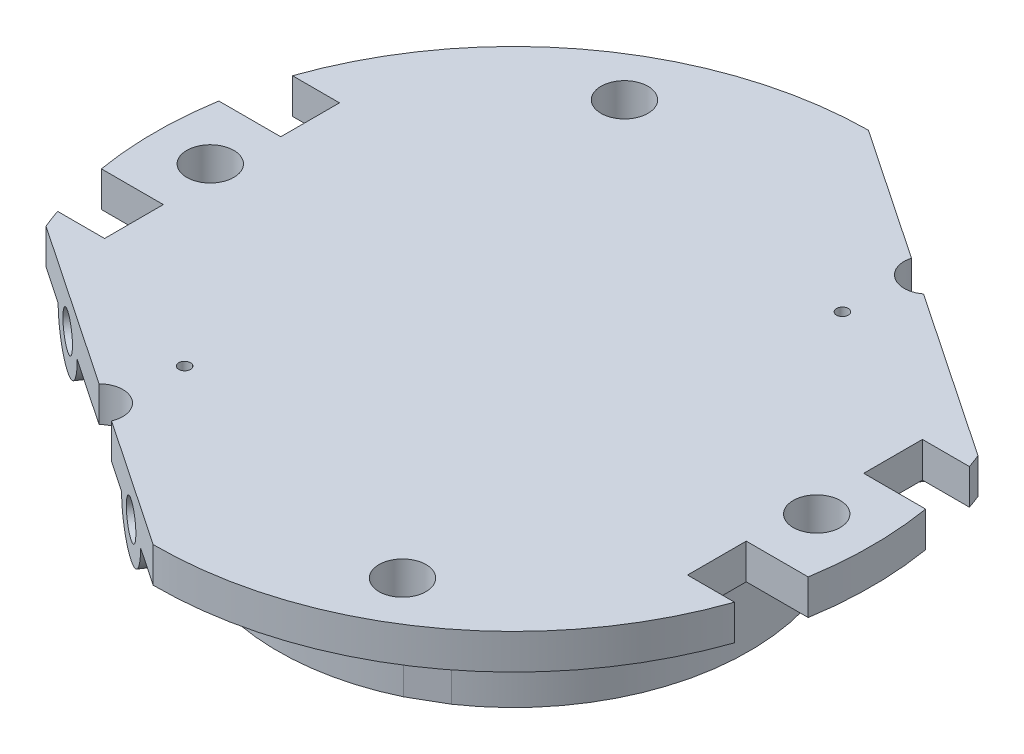
SolidWorks part; units mm, degrees
ref_plane "Alzado" through (0, 0, 0) normal (0, 0, 1) x (1, 0, 0)
ref_plane "Planta" through (0, 0, 0) normal (0, 1, 0) x (1, 0, 0)
ref_plane "Vista lateral" through (0, 0, 0) normal (1, 0, 0) x (0, 0, -1)
sketch "Croquis1" plane through (0, 0, 0) normal (0, 1, 0) x (1, 0, 0)
  circle A0 centre (0, 0) radius 30.5
extrude "Saliente-Extruir1" add sketch "Croquis1" along normal blind 3
sketch "Croquis5" plane through (0, 3, 0) normal (0, 1, 0) x (1, 0, 0)
  line L1 (28.8141, -5) -> (30.0874, -5)
  line L2 (28.8141, 5) -> (30.0874, 5)
  line L3 (-24.8141, 10) -> (-28.8141, 10)
  line L4 (24.8141, -5) -> (24.8141, -10)
  line L5 (-24.8141, -10) -> (-28.8141, -10)
  line L6 (24.8141, -5) -> (28.8141, -5)
  line L7 (24.8141, 5) -> (24.8141, 10)
  line L8 (-24.8141, 5) -> (-28.8141, 5)
  line L9 (-24.8141, 5) -> (-24.8141, 10)
  line L10 (-24.8141, -5) -> (-28.8141, -5)
  line L11 (-24.8141, -5) -> (-24.8141, -10)
  line L12 (24.8141, 5) -> (28.8141, 5)
  line L13 (24.8141, -10) -> (28.8141, -10)
  line L14 (24.8141, 10) -> (28.8141, 10)
  line L15 (-28.8141, 5) -> (-30.0874, 5)
  line L16 (-28.8141, -5) -> (-30.0874, -5)
  line L18 (-24.8141, 0) -> (-12.407, -21.4896)
  line L19 (-12.407, -21.4896) -> (12.407, -21.4896)
  line L20 (12.407, -21.4896) -> (24.8141, 0)
  line L21 (24.8141, 0) -> (12.407, 21.4896)
  line L22 (12.407, 21.4896) -> (-12.407, 21.4896)
  line L23 (-12.407, 21.4896) -> (-24.8141, 0)
  circle A0 centre (0, 0) radius 21.4896 construction
  circle A1 centre (0, 0) radius 30.5 construction
  arc A2 (-28.8141, 10) -> (-30.0874, 5) centre (0, 0) ccw
  arc A4 (-30.0874, -5) -> (-28.8141, -10) centre (0, 0) ccw
  arc A5 (30.0874, -5) -> (28.8141, -10) centre (0, 0) cw
  arc A6 (28.8141, 10) -> (30.0874, 5) centre (0, 0) cw
  circle M2 centre (0, 0) radius 30.5
extrude "Cortar-Extruir3" cut sketch "Croquis5" against normal blind 4 contours L10 L16 L5 L11 M2 | L15 L8 L9 L3 M2 | L14 L7 L12 L2 M2 | L4 L13 L1 L6 M2
sketch "Croquis7" plane through (0, 3, 0) normal (0, 1, 0) x (1, 0, 0)
  line L2 (25.8141, 0) -> (12.907, 22.3556)
  line L3 (12.907, 22.3556) -> (-12.907, 22.3556)
  line L4 (-12.907, 22.3556) -> (-25.8141, 0)
  line L5 (-25.8141, 0) -> (-12.907, -22.3556)
  line L6 (-12.907, -22.3556) -> (12.907, -22.3556)
  line L7 (12.907, -22.3556) -> (25.8141, 0)
  circle A0 centre (25.8141, 0) radius 2
  circle A4 centre (-25.8141, 0) radius 2
  circle A5 centre (0, 0) radius 22.3556 construction
  circle A6 centre (12.907, 22.3556) radius 2
  circle A7 centre (-12.907, -22.3556) radius 2
  circle A8 centre (-12.907, 22.3556) radius 2
  circle A9 centre (12.907, -22.3556) radius 2
extrude "Cortar-Extruir4" cut sketch "Croquis7" against normal blind 10 contours A8 L4 L3 | A4 L4 L5 | A4 L5 L4 | A8 L3 L4 | L2 A6 L3 | L3 A6 L2 | L7 A0 L2 | L2 A0 L7 | A7 L5 L6 | A7 L6 L5 | L6 A9 L7 | L7 A9 L6
sketch "Croquis8" plane through (0, 3, 0) normal (0, 1, 0) x (1, 0, 0)
  line L0 (0, 0) -> (12, 0)
  line L1 (12, 0) -> (12, 16)
  line L2 (0, 0) -> (-12, 0)
  line L3 (-12, 0) -> (-12, -16)
  circle A0 centre (12, 16) radius 0.5
  circle A1 centre (-12, -16) radius 0.5
extrude "Cortar-Extruir5" cut sketch "Croquis8" against normal blind 3
sketch "Croquis9" plane through (0, 3, 0) normal (0, 1, 0) x (1, 0, 0)
  line L2 (-10, 17.3205) -> (-8.701, 18.0705)
  line L5 (25.6318, 16.5306) -> (27.1318, 13.9325)
  line L6 (-10, 17.3205) -> (-11.299, 16.5705)
  line L8 (10, -17.3205) -> (8.701, -18.0705)
  line L9 (10, -17.3205) -> (11.299, -16.5705)
  circle A0 centre (0, 0) radius 20.0562
  circle A1 centre (-12, -16) radius 3
  circle A2 centre (12, 16) radius 3
extrude "Saliente-Extruir2" add sketch "Croquis9" against normal blind 13
sketch "Croquis11" plane through (14.0495, 0, -20.8293) normal (0.5592, 0, -0.829) x (-0.829, 0, -0.5592)
  line L1 (17.2916, 0) -> (-17.2916, 0)
  line L2 (17.2916, 0) -> (17.2916, 3)
  line L3 (17.2916, 3) -> (-17.2916, 3)
  line L4 (-17.2916, 0) -> (-17.2916, 3)
extrude "Saliente-Extruir3" add sketch "Croquis11" along normal blind 6
sketch "Croquis12" plane through (0, 3, 0) normal (0, 1, 0) x (1, 0, 0)
  circle A0 centre (12.907, 22.3556) radius 2
extrude "Cortar-Extruir7" cut sketch "Croquis12" against normal blind 3
sketch "Croquis13" plane through (17.4047, 0, -25.8035) normal (0.5592, 0, -0.829) x (-0.829, 0, -0.5592)
  line L0 (-17.2916, 0) -> (17.2916, 0)
  line L1 (17.2916, 3) -> (-17.2916, 3)
  line L2 (17.2916, 3) -> (-17.2916, 3) construction
  line L3 (17.2916, 0) -> (17.2916, 3) construction
  circle A1 centre (10, 0) radius 3
  circle A2 centre (-10, 0) radius 3
  circle A3 centre (10, 0) radius 1.5
  circle A5 centre (-10, 0) radius 1.5
  line M4 (-17.2916, 0) -> (17.2916, 0)
extrude "Saliente-Extruir4" add sketch "Croquis13" against normal blind 20 contours A3 L0 A1 | A3 L0 A1 | A5 L0 A2 | A5 L0 A2 | A5 M4 | A3 M4
sketch "Croquis14" plane through (17.4047, 0, -25.8035) normal (0.5592, 0, -0.829) x (-0.829, 0, -0.5592)
  circle A0 centre (-10, 0) radius 1.5
  circle A1 centre (10, 0) radius 1.5
extrude "Cortar-Extruir8" cut sketch "Croquis14" against normal blind 6
sketch "Croquis15" plane through (0, 3, 0) normal (0, 1, 0) x (1, 0, 0)
  line L0 (28.3849, 11.16) -> (-0.2859, 30.4987)
  line L1 (28.3849, 11.16) -> (0.1409, -30.7136)
  line L2 (-0.2859, 30.4987) -> (-28.5299, -11.3749)
  line L3 (0.1409, -30.7136) -> (-28.5299, -11.3749)
  circle A0 centre (-0.2859, 0) radius 30.7165
  arc M12 (-28.8141, -10) -> (28.8141, -10) centre (0, 0) ccw
  circle M28 centre (-12.907, -22.3556) radius 2
extrude "Cortar-Extruir9" cut sketch "Croquis15" against normal blind 3 contours L3 M12 M28
sketch "Croquis16" plane through (-14.1945, 0, 21.0442) normal (-0.5592, 0, 0.829) x (0.829, 0, 0.5592)
  line L0 (-16.9088, 0) -> (-16.9088, 3)
  line L1 (-16.9088, 0) -> (16.78, 0)
  line L2 (-16.9088, 3) -> (16.78, 3)
  line L3 (16.78, 0) -> (16.78, 3)
extrude "Saliente-Extruir5" add sketch "Croquis16" along normal blind 6
sketch "Croquis17" plane through (0, 3, 0) normal (0, 1, 0) x (1, 0, 0)
  circle A0 centre (-12.907, -22.3556) radius 2
extrude "Cortar-Extruir10" cut sketch "Croquis17" against normal blind 3
sketch "Croquis18" plane through (-17.5497, 0, 26.0185) normal (-0.5592, 0, 0.829) x (0.829, 0, 0.5592)
  line L2 (-16.9088, 0) -> (16.78, 0) construction
  circle A0 centre (9.9356, 0) radius 3
  circle A1 centre (-10.0644, 0) radius 3
extrude "Saliente-Extruir6" add sketch "Croquis18" against normal blind 25
sketch "Croquis19" plane through (-17.5497, 0, 26.0185) normal (-0.5592, 0, 0.829) x (0.829, 0, 0.5592)
  circle A0 centre (-10.0644, 0) radius 1.5
  circle A1 centre (9.9356, 0) radius 1.5
extrude "Cortar-Extruir11" cut sketch "Croquis19" against normal blind 5
sketch "Croquis20" plane through (17.4047, 0, -25.8035) normal (0.5592, 0, -0.829) x (-0.829, 0, -0.5592)
  line L0 (17.2916, 3) -> (17.2916, 0)
  line L1 (17.2916, 0) -> (13, 0)
  line L2 (-7, 0) -> (7, 0) construction
  line L3 (7, 0) -> (-7, 0)
  line L4 (-13, 0) -> (-17.2916, 0)
  line L5 (-17.2916, 0) -> (-17.2916, 3)
  line L6 (-17.2916, 3) -> (17.2916, 3)
  arc A0 (13, 0) -> (7, 0) centre (10, 0) cw
  arc A1 (7, 0) -> (13, 0) centre (10, 0) ccw construction
  arc A2 (-7, 0) -> (-13, 0) centre (-10, 0) cw
extrude "Cortar-Extruir12" cut sketch "Croquis20" against normal blind 6
sketch "Croquis21" plane through (-17.5497, 0, 26.0185) normal (-0.5592, 0, 0.829) x (0.829, 0, 0.5592)
  line L0 (-13.0644, 0) -> (-16.9088, 0)
  line L1 (-16.9088, 0) -> (-16.9088, 3)
  line L2 (-16.9088, 3) -> (16.78, 3)
  line L3 (16.78, 3) -> (16.78, 0)
  line L4 (16.78, 0) -> (12.9356, 0)
  line L5 (6.9356, 0) -> (-7.0644, 0)
  arc A0 (-13.0644, 0) -> (-7.0644, 0) centre (-10.0644, 0) ccw
  arc A1 (6.9356, 0) -> (12.9356, 0) centre (9.9356, 0) ccw
extrude "Cortar-Extruir13" cut sketch "Croquis21" against normal blind 6
sketch "Croquis22" plane through (-14.1945, 0, 21.0442) normal (-0.5592, 0, 0.829) x (0.829, 0, 0.5592)
  circle A0 centre (-10.0644, 0) radius 1.5
  circle A1 centre (9.9356, 0) radius 1.5
extrude "Cortar-Extruir14" cut sketch "Croquis22" against normal blind 6
sketch "Croquis23" plane through (14.0495, 0, -20.8293) normal (0.5592, 0, -0.829) x (-0.829, 0, -0.5592)
  circle A0 centre (-10, 0) radius 1.5
  circle A1 centre (10, 0) radius 1.5
extrude "Cortar-Extruir15" cut sketch "Croquis23" against normal blind 6
sketch "Croquis25" plane through (0, 3, 0) normal (0, 1, 0) x (1, 0, 0)
  line L0 (-0.2859, 30.4987) -> (28.3849, 11.16)
  line L1 (-0.2859, 30.4987) -> (16.4899, 55.3698)
  line L2 (28.3849, 11.16) -> (45.1607, 36.0311)
  line L3 (16.4899, 55.3698) -> (45.1607, 36.0311)
  line L4 (-28.2125, -11.589) -> (-0.1765, -30.4995)
  line L5 (-28.2125, -11.589) -> (-44.9883, -36.4601)
  line L6 (-0.1765, -30.4995) -> (-16.9523, -55.3706)
  line L7 (-44.9883, -36.4601) -> (-16.9523, -55.3706)
  circle A0 centre (0, 0) radius 33
  circle A1 centre (-12.907, -22.3556) radius 2
  circle A2 centre (12.907, 22.3556) radius 2
